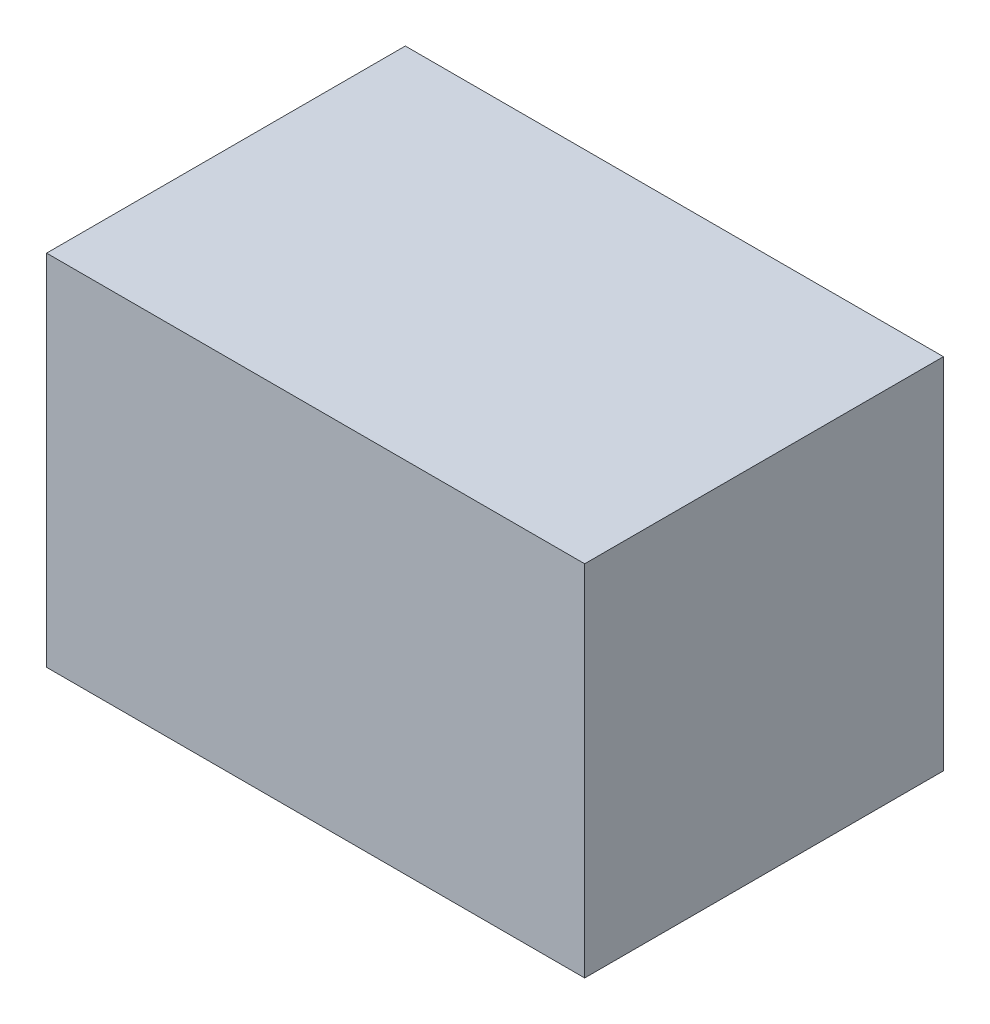
SolidWorks part; units mm, degrees
ref_plane "Front Plane" through (0, 0, 0) normal (0, 0, 1) x (1, 0, 0)
ref_plane "Top Plane" through (0, 0, 0) normal (0, 1, 0) x (1, 0, 0)
ref_plane "Right Plane" through (0, 0, 0) normal (1, 0, 0) x (0, 0, -1)
sketch "Sketch1" plane through (0, 0, 0) normal (0, 1, 0) x (1, 0, 0)
  line L1 (-75, -50) -> (75, -50)
  line L2 (-75, -50) -> (-75, 50)
  line L3 (-75, 50) -> (75, 50)
  line L4 (75, -50) -> (75, 50)
  line L5 (-75, -50) -> (75, 50) construction
  line L6 (-75, 50) -> (75, -50) construction
  point P0 (0, 0)
  dimension "D1" = 150
  dimension "D2" = 100
extrude "Boss-Extrude1" add sketch "Sketch1" along normal blind 100
